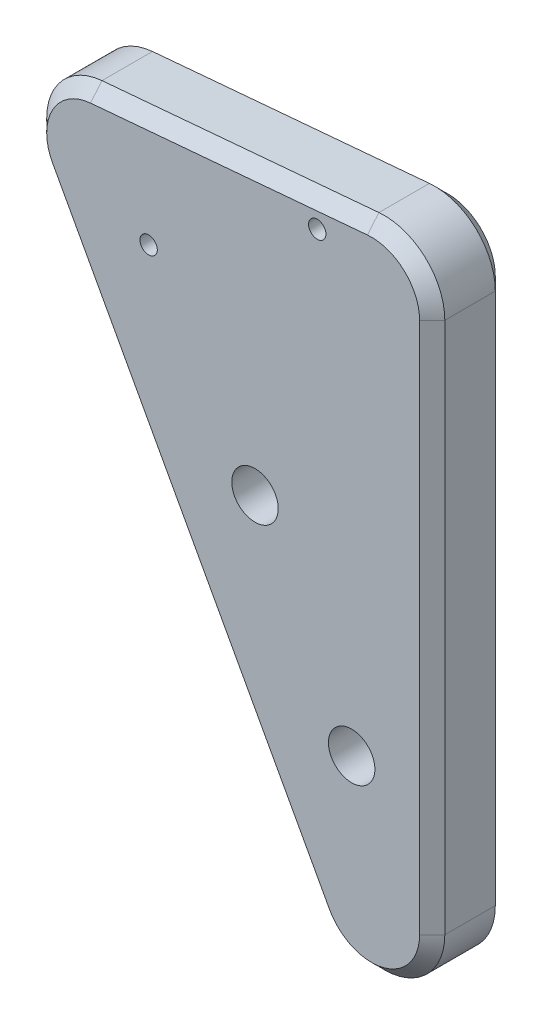
SolidWorks part; units mm, degrees
ref_plane "Front Plane" through (0, 0, 0) normal (0, 0, 1) x (1, 0, 0)
ref_plane "Top Plane" through (0, 0, 0) normal (0, 1, 0) x (1, 0, 0)
ref_plane "Right Plane" through (0, 0, 0) normal (1, 0, 0) x (0, 0, -1)
sketch "Sketch1" plane through (0, 0, 0) normal (0, 0, 1) x (1, 0, 0)
  line L0 (0, 0) -> (54.7145, -100.3535)
  line L1 (54.7145, -100.3535) -> (54.7145, 4.7869)
  line L3 (0, 0) -> (54.7145, 4.7869)
  line L4 (0, 0) -> (100.7995, 0) construction
  line L5 (33.4366, -61.3271) -> (80.8296, -35.4876) construction
  line L6 (19.05, -12.3567) -> (17.5047, 5.3065) construction
  circle A0 centre (44.587, -55.2477) radius 2.921
  circle A1 centre (32.4282, -32.947) radius 2.921
  circle A2 centre (40.2575, -0.0475) radius 1.0922
  circle A3 centre (19.05, -12.3567) radius 1.0922
  point P15 (0, 0)
  dimension "D4" = 5.842
  dimension "D8" = 2.1844
  dimension "D1" = 28.6
  dimension "D2" = 5
  dimension "D3" = 114.3
  dimension "D5" = 25.4
  dimension "D6" = 12.7
  dimension "D7" = 12.7
  dimension "D9" = 3.556
  dimension "D10" = 13.97
  dimension "D11" = 22.1996
  dimension "D12" = 19.05
  dimension "D13" = 44.45
extrude "Boss-Extrude1" add sketch "Sketch1" along normal blind 9.525
fillet "Fillet1" radius 7.62 3 edges at (54.7145, -100.3535, 4.7625) (0, 0, 4.7625) (54.7145, 4.7869, 4.7625)
chamfer "Chamfer1" distance 1.5875 angle 45 12 edges at (5.5489, -2.9753, 0) (22.9892, -42.1652, 0) (48.9766, -77.8429, 0) (54.7145, -36.9939, 0) (29.0153, 2.5385, 0) (52.2425, 2.0892, 0) (48.9766, -77.8429, 9.525) (22.9892, -42.1652, 9.525) (5.5489, -2.9753, 9.525) (29.0153, 2.5385, 9.525) (52.2425, 2.0892, 9.525) (54.7145, -36.9939, 9.525)
